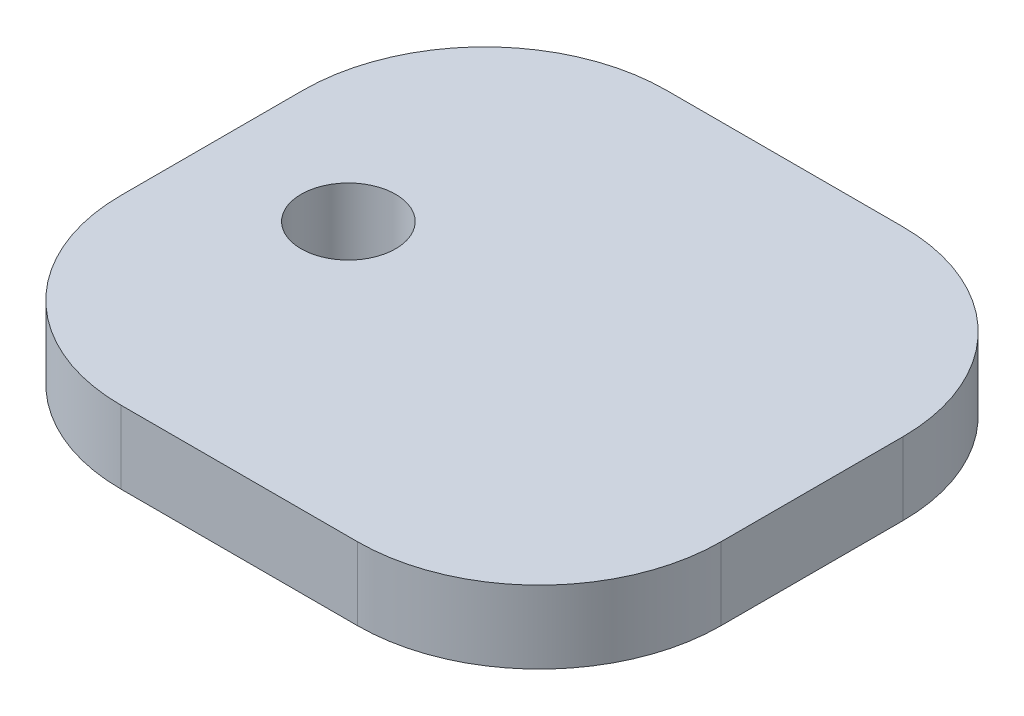
SolidWorks part; units mm, degrees
ref_plane "Front Plane" through (0, 0, 0) normal (0, 0, 1) x (1, 0, 0)
ref_plane "Top Plane" through (0, 0, 0) normal (0, 1, 0) x (1, 0, 0)
ref_plane "Right Plane" through (0, 0, 0) normal (1, 0, 0) x (0, 0, -1)
sketch "Sketch1" plane through (0, 0, 0) normal (0, 1, 0) x (1, 0, 0)
  line L1 (-19.5, 15) -> (13.5, 15)
  line L2 (-19.5, 15) -> (-19.5, -15)
  line L3 (-19.5, -15) -> (13.5, -15)
  line L4 (13.5, 15) -> (13.5, -15)
  line L5 (-19.5, 15) -> (13.5, -15) construction
  line L6 (-19.5, -15) -> (13.5, 15) construction
  circle A0 centre (-12, 0) radius 2.6
  point P0 (-3, 0)
  dimension "D3" = 5.2
  dimension "D1" = 33
  dimension "D2" = 30
  dimension "D4" = 12
  dimension "D5" = 3
extrude "Boss-Extrude1" add sketch "Sketch1" along normal blind 4
fillet "Fillet1" radius 10 4 edges at (-19.5, 2, -15) (13.5, 2, -15) (13.5, 2, 15) (-19.5, 2, 15)
